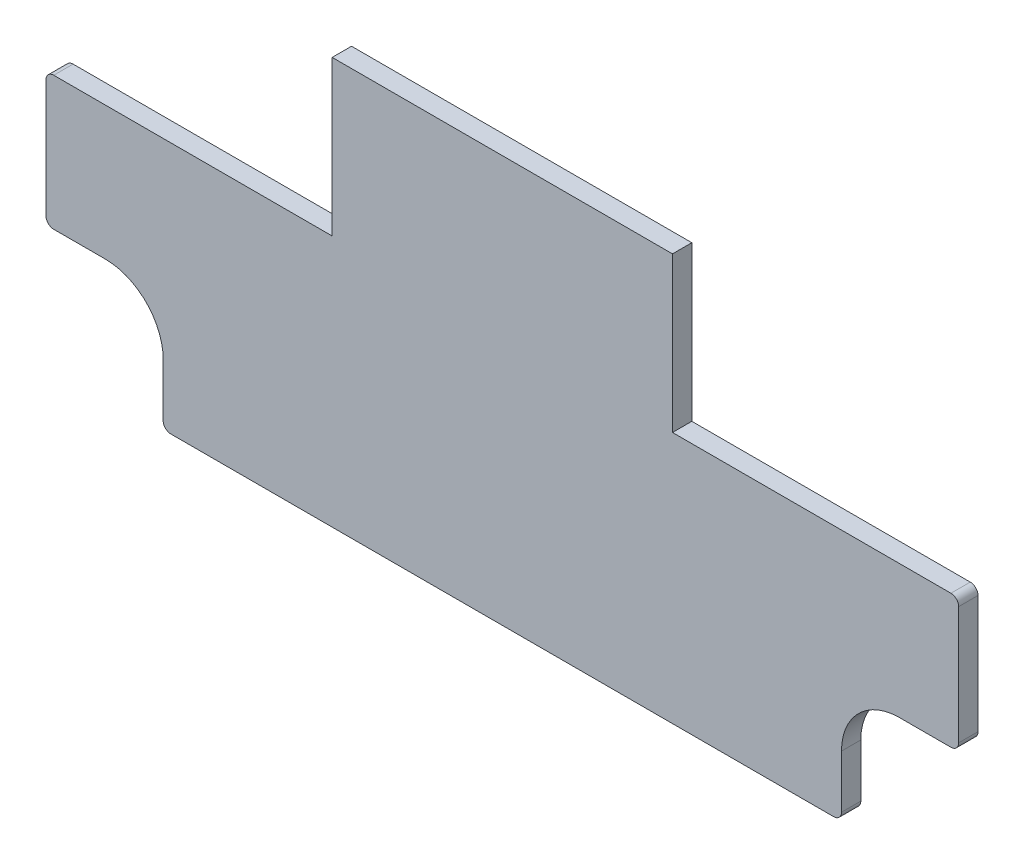
SolidWorks part; units mm, degrees
ref_plane "Plan de face" through (0, 0, 0) normal (0, 0, 1) x (1, 0, 0)
ref_plane "Plan de dessus" through (0, 0, 0) normal (0, 1, 0) x (1, 0, 0)
ref_plane "Plan de droite" through (0, 0, 0) normal (1, 0, 0) x (0, 0, -1)
sketch "Esquisse1" plane through (0, 0, 0) normal (0, 0, 1) x (1, 0, 0)
  line L0 (0, 0) -> (236, 0)
  line L1 (236, 0) -> (236, 65.2)
  line L2 (236, 65.2) -> (162, 65.2)
  line L3 (162, 65.2) -> (162, 105.2)
  line L4 (162, 105.2) -> (74, 105.2)
  line L5 (74, 105.2) -> (74, 65.2)
  line L6 (74, 65.2) -> (0, 65.2)
  line L7 (0, 65.2) -> (0, 0)
  line L8 (0, 30.7) -> (33, 30.7)
  line L10 (236, 30.7) -> (203, 30.7)
  line L12 (30.3, 30.7) -> (30.3, 0)
  line L13 (205.7, 30.7) -> (205.7, 0)
  circle A0 centre (15.3, 15.7) radius 15
  circle A1 centre (220.7, 15.7) radius 15
  dimension "D8" = 30
  dimension "D12" = 30
  dimension "D1" = 88
  dimension "D2" = 74
  dimension "D3" = 74
  dimension "D4" = 65.2
  dimension "D6" = 30.7
  dimension "D7" = 15.7
  dimension "D9" = 43.7
  dimension "D10" = 33
  dimension "D11" = 15.7
  dimension "D13" = 40
  dimension "D14" = 65.2
  dimension "D28" = 15
  dimension "D30" = 15
  dimension "D43" = 30.7
extrude "Boss.-Extru.1" add sketch "Esquisse1" along normal blind 5
fillet "Congé1" radius 2 6 edges at (0, 65.2, 2.5) (0, 30.7, 2.5) (30.3, 0, 2.5) (205.7, 0, 2.5) (236, 30.7, 2.5) (236, 65.2, 2.5)
